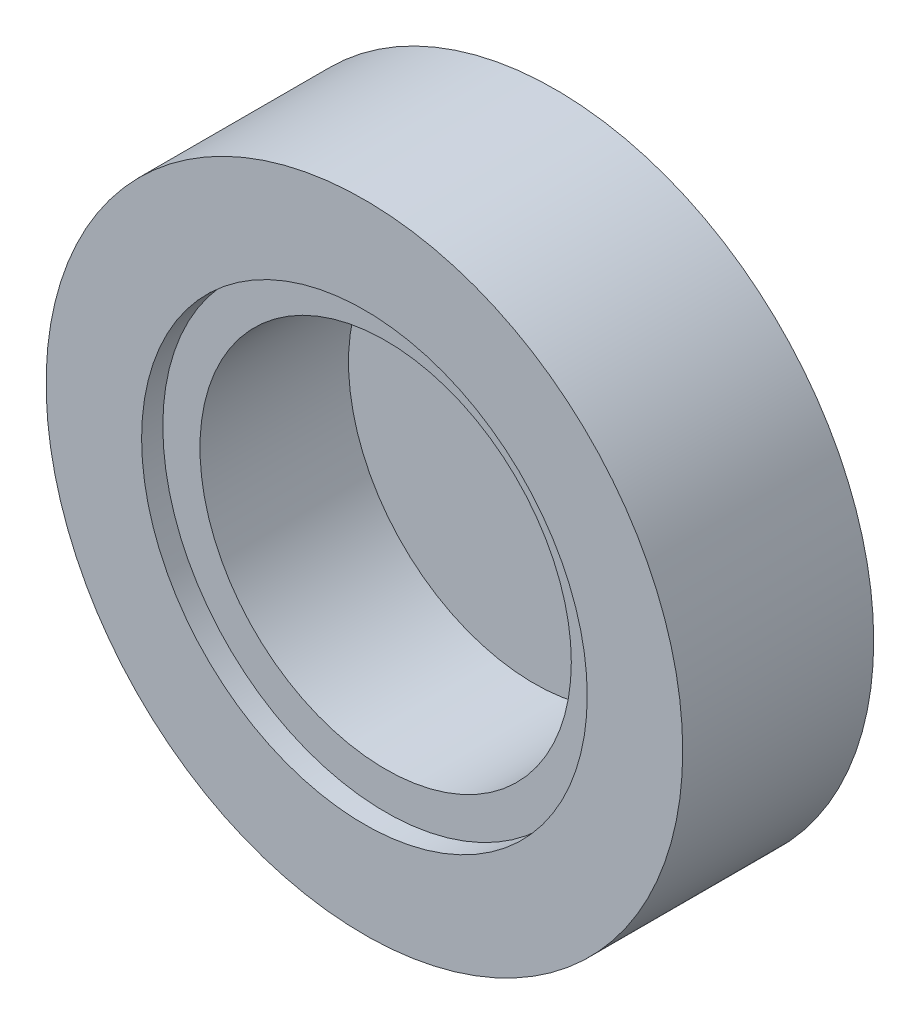
SolidWorks part; units mm, degrees
ref_plane "Front Plane" through (0, 0, 0) normal (0, 0, 1) x (1, 0, 0)
ref_plane "Top Plane" through (0, 0, 0) normal (0, 1, 0) x (1, 0, 0)
ref_plane "Right Plane" through (0, 0, 0) normal (1, 0, 0) x (0, 0, -1)
sketch "Sketch1" plane through (0, 0, 0) normal (0, 0, 1) x (1, 0, 0)
  circle A0 centre (0, 0) radius 30
  dimension "D1" = 60
extrude "Boss-Extrude1" add sketch "Sketch1" along normal blind 18
sketch "Sketch2" plane through (0, 0, 18) normal (0, 0, 1) x (1, 0, 0)
  circle A0 centre (0, 0) radius 17.5
  dimension "D1" = 35
extrude "Cut-Extrude1" cut sketch "Sketch2" against normal blind 16
sketch "Sketch4" plane through (0, 0, 18) normal (0, 0, 1) x (1, 0, 0)
  circle A0 centre (0, 0) radius 21
  dimension "D1" = 42
extrude "Cut-Extrude2" cut sketch "Sketch4" against normal blind 2
